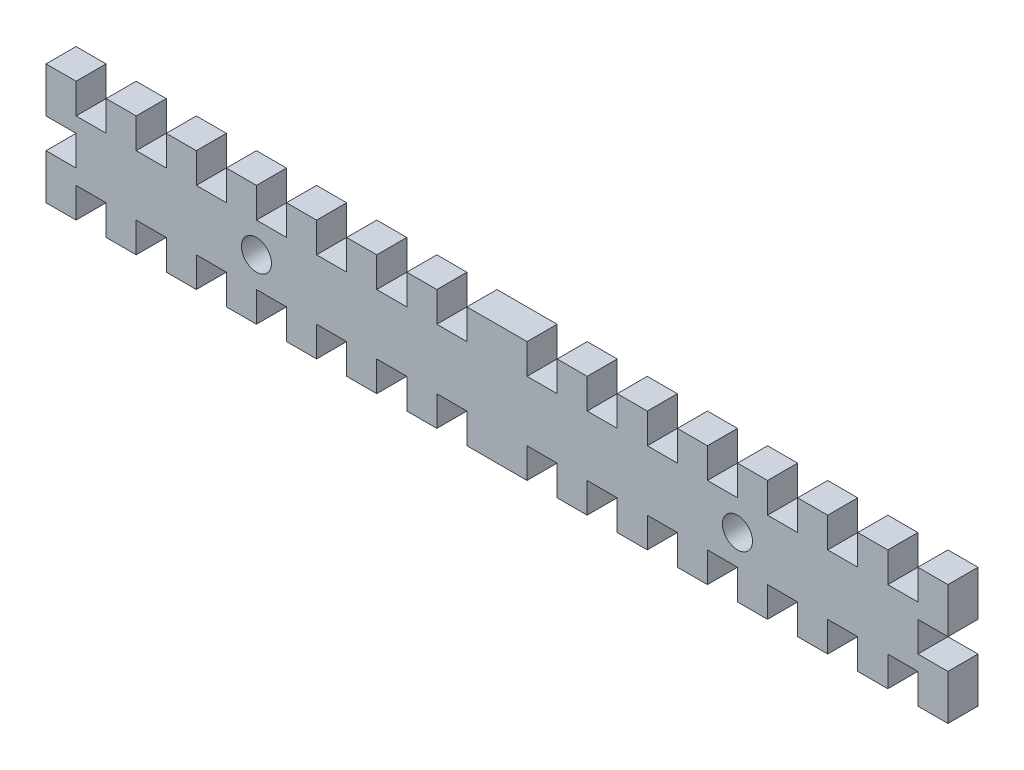
SolidWorks part; units mm, degrees
ref_plane "Front Plane" through (0, 0, 0) normal (0, 0, 1) x (1, 0, 0)
ref_plane "Top Plane" through (0, 0, 0) normal (0, 1, 0) x (1, 0, 0)
ref_plane "Right Plane" through (0, 0, 0) normal (1, 0, 0) x (0, 0, -1)
sketch "Sketch1" plane through (0, 0, 0) normal (0, 0, 1) x (1, 0, 0)
  line L0 (0, 7.8403) -> (0, -5.9477) construction
  line L1 (-95.25, 12.7) -> (-88.9, 12.7)
  line L2 (-95.25, 12.7) -> (-95.25, 3.175)
  line L3 (-95.25, -12.7) -> (-88.9, -12.7)
  line L4 (95.25, 12.7) -> (95.25, 3.175)
  line L5 (-95.25, 12.7) -> (95.25, -12.7) construction
  line L6 (-95.25, -12.7) -> (95.25, 12.7) construction
  line L7 (0, 0) -> (50.8, 0) construction
  line L8 (0, 0) -> (-50.8, 0) construction
  line L9 (95.25, 16.1654) -> (88.9, 16.1654) construction
  line L10 (88.9, 12.7) -> (88.9, 6.35)
  line L11 (88.9, 6.35) -> (82.55, 6.35)
  line L12 (82.55, 6.35) -> (82.55, 12.7)
  line L13 (69.85, 6.35) -> (69.85, 12.7)
  line L14 (76.2, 6.35) -> (69.85, 6.35)
  line L15 (76.2, 12.7) -> (76.2, 6.35)
  line L16 (57.15, 6.35) -> (57.15, 12.7)
  line L17 (63.5, 6.35) -> (57.15, 6.35)
  line L18 (63.5, 12.7) -> (63.5, 6.35)
  line L19 (44.45, 6.35) -> (44.45, 12.7)
  line L20 (50.8, 6.35) -> (44.45, 6.35)
  line L21 (50.8, 12.7) -> (50.8, 6.35)
  line L22 (31.75, 6.35) -> (31.75, 12.7)
  line L23 (38.1, 6.35) -> (31.75, 6.35)
  line L24 (38.1, 12.7) -> (38.1, 6.35)
  line L25 (19.05, 6.35) -> (19.05, 12.7)
  line L26 (25.4, 6.35) -> (19.05, 6.35)
  line L27 (25.4, 12.7) -> (25.4, 6.35)
  line L28 (6.35, 6.35) -> (6.35, 12.7)
  line L29 (12.7, 6.35) -> (6.35, 6.35)
  line L30 (12.7, 12.7) -> (12.7, 6.35)
  line L31 (-88.9, 12.7) -> (-88.9, 6.35)
  line L32 (-88.9, 6.35) -> (-82.55, 6.35)
  line L33 (-82.55, 6.35) -> (-82.55, 12.7)
  line L34 (88.9, -12.7) -> (88.9, -6.35)
  line L35 (88.9, -6.35) -> (82.55, -6.35)
  line L36 (82.55, -6.35) -> (82.55, -12.7)
  line L37 (-88.9, -12.7) -> (-88.9, -6.35)
  line L38 (-82.55, -6.35) -> (-82.55, -12.7)
  line L39 (-88.9, -6.35) -> (-82.55, -6.35)
  line L40 (69.85, -6.35) -> (69.85, -12.7)
  line L41 (76.2, -6.35) -> (69.85, -6.35)
  line L42 (76.2, -12.7) -> (76.2, -6.35)
  line L43 (57.15, -6.35) -> (57.15, -12.7)
  line L44 (63.5, -6.35) -> (57.15, -6.35)
  line L45 (63.5, -12.7) -> (63.5, -6.35)
  line L46 (44.45, -6.35) -> (44.45, -12.7)
  line L47 (50.8, -6.35) -> (44.45, -6.35)
  line L48 (50.8, -12.7) -> (50.8, -6.35)
  line L49 (31.75, -6.35) -> (31.75, -12.7)
  line L50 (38.1, -6.35) -> (31.75, -6.35)
  line L51 (38.1, -12.7) -> (38.1, -6.35)
  line L52 (19.05, -6.35) -> (19.05, -12.7)
  line L53 (25.4, -6.35) -> (19.05, -6.35)
  line L54 (25.4, -12.7) -> (25.4, -6.35)
  line L55 (6.35, -6.35) -> (6.35, -12.7)
  line L56 (12.7, -6.35) -> (6.35, -6.35)
  line L57 (12.7, -12.7) -> (12.7, -6.35)
  line L58 (-69.85, -6.35) -> (-69.85, -12.7)
  line L59 (-76.2, -6.35) -> (-69.85, -6.35)
  line L60 (-76.2, -12.7) -> (-76.2, -6.35)
  line L61 (-57.15, -6.35) -> (-57.15, -12.7)
  line L62 (-63.5, -6.35) -> (-57.15, -6.35)
  line L63 (-63.5, -12.7) -> (-63.5, -6.35)
  line L64 (-44.45, -6.35) -> (-44.45, -12.7)
  line L65 (-50.8, -6.35) -> (-44.45, -6.35)
  line L66 (-50.8, -12.7) -> (-50.8, -6.35)
  line L67 (-31.75, -6.35) -> (-31.75, -12.7)
  line L68 (-38.1, -6.35) -> (-31.75, -6.35)
  line L69 (-38.1, -12.7) -> (-38.1, -6.35)
  line L70 (-19.05, -6.35) -> (-19.05, -12.7)
  line L71 (-25.4, -6.35) -> (-19.05, -6.35)
  line L72 (-25.4, -12.7) -> (-25.4, -6.35)
  line L73 (-6.35, -6.35) -> (-6.35, -12.7)
  line L74 (-12.7, -6.35) -> (-6.35, -6.35)
  line L75 (-12.7, -12.7) -> (-12.7, -6.35)
  line L76 (-76.2, 12.7) -> (-76.2, 6.35)
  line L77 (-76.2, 6.35) -> (-69.85, 6.35)
  line L78 (-69.85, 6.35) -> (-69.85, 12.7)
  line L79 (-63.5, 12.7) -> (-63.5, 6.35)
  line L80 (-63.5, 6.35) -> (-57.15, 6.35)
  line L81 (-57.15, 6.35) -> (-57.15, 12.7)
  line L82 (-50.8, 12.7) -> (-50.8, 6.35)
  line L83 (-50.8, 6.35) -> (-44.45, 6.35)
  line L84 (-44.45, 6.35) -> (-44.45, 12.7)
  line L85 (-38.1, 12.7) -> (-38.1, 6.35)
  line L86 (-38.1, 6.35) -> (-31.75, 6.35)
  line L87 (-31.75, 6.35) -> (-31.75, 12.7)
  line L88 (-25.4, 12.7) -> (-25.4, 6.35)
  line L89 (-25.4, 6.35) -> (-19.05, 6.35)
  line L90 (-19.05, 6.35) -> (-19.05, 12.7)
  line L91 (-12.7, 12.7) -> (-12.7, 6.35)
  line L92 (-12.7, 6.35) -> (-6.35, 6.35)
  line L93 (-6.35, 6.35) -> (-6.35, 12.7)
  line L94 (-82.55, -12.7) -> (-76.2, -12.7)
  line L95 (-69.85, -12.7) -> (-63.5, -12.7)
  line L96 (-57.15, -12.7) -> (-50.8, -12.7)
  line L97 (-44.45, -12.7) -> (-38.1, -12.7)
  line L98 (-31.75, -12.7) -> (-25.4, -12.7)
  line L99 (-19.05, -12.7) -> (-12.7, -12.7)
  line L100 (-6.35, -12.7) -> (19.05, -12.7)
  line L101 (25.4, -12.7) -> (31.75, -12.7)
  line L102 (38.1, -12.7) -> (44.45, -12.7)
  line L103 (50.8, -12.7) -> (57.15, -12.7)
  line L104 (63.5, -12.7) -> (69.85, -12.7)
  line L105 (76.2, -12.7) -> (82.55, -12.7)
  line L106 (88.9, -12.7) -> (95.25, -12.7)
  line L107 (88.9, 12.7) -> (95.25, 12.7)
  line L108 (76.2, 12.7) -> (82.55, 12.7)
  line L109 (63.5, 12.7) -> (69.85, 12.7)
  line L110 (50.8, 12.7) -> (57.15, 12.7)
  line L111 (38.1, 12.7) -> (44.45, 12.7)
  line L112 (25.4, 12.7) -> (31.75, 12.7)
  line L113 (12.7, 12.7) -> (19.05, 12.7)
  line L114 (-6.35, 12.7) -> (6.35, 12.7)
  line L115 (-19.05, 12.7) -> (-12.7, 12.7)
  line L116 (-31.75, 12.7) -> (-25.4, 12.7)
  line L117 (-44.45, 12.7) -> (-38.1, 12.7)
  line L118 (-57.15, 12.7) -> (-50.8, 12.7)
  line L119 (-69.85, 12.7) -> (-63.5, 12.7)
  line L120 (-82.55, 12.7) -> (-76.2, 12.7)
  line L121 (102.1723, 12.7) -> (102.1723, 3.175) construction
  line L122 (95.25, 3.175) -> (88.9, 3.175)
  line L123 (88.9, 3.175) -> (88.9, -3.175)
  line L124 (88.9, -3.175) -> (95.25, -3.175)
  line L125 (103.8428, -12.7) -> (103.8428, -3.175) construction
  line L126 (-88.9, -3.175) -> (-95.25, -3.175)
  line L127 (-88.9, 3.175) -> (-88.9, -3.175)
  line L128 (-95.25, 3.175) -> (-88.9, 3.175)
  line L129 (-95.25, -3.175) -> (-95.25, -12.7)
  line L130 (95.25, -3.175) -> (95.25, -12.7)
  circle A0 centre (-50.8, 0) radius 3.175
  circle A1 centre (50.8, 0) radius 3.175
  point P0 (0, 0)
  dimension "D1" = 6.35
  dimension "D2" = 6.35
  dimension "D3" = 7
extrude "Boss-Extrude1" add sketch "Sketch1" along normal blind 6.35 contours L130 L124 L123 L122 L4 L107 L10 L11 L12 L108 L15 L14 L13 L109 L18 L17 L16 L110 L21 L20 L19 L111 L24 L23 L22 L112 L27 L26 L25 L113 L30 L29 L28 L114 L93 L92 L91 L115 L90 L89 L88 L116 L87 L86 L85 L117 L84 L83 L82 L118 L81
